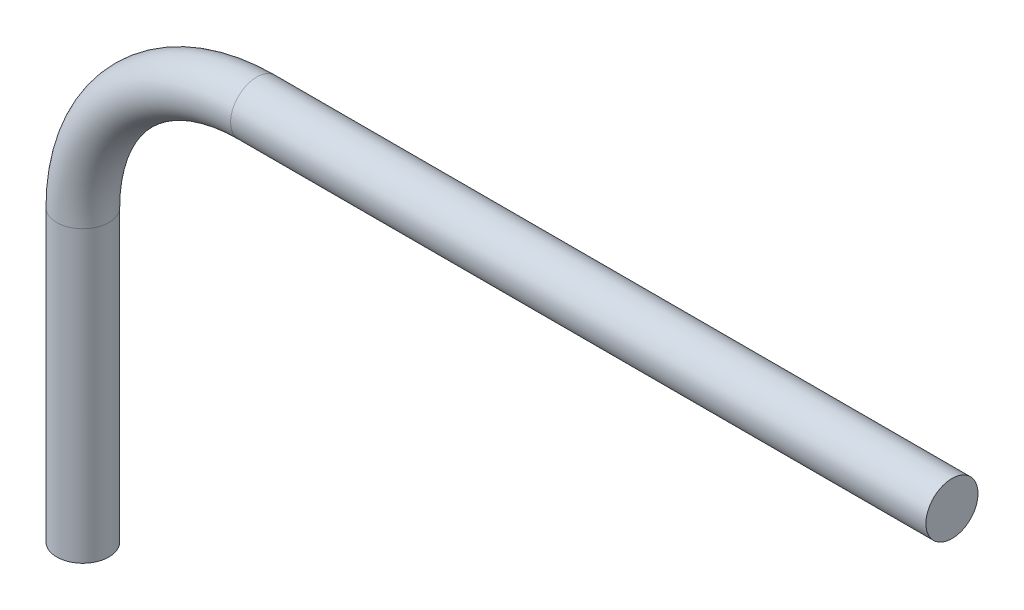
SolidWorks part; units mm, degrees
material "AISI 316 Stainless Steel Sheet (SS)"
ref_plane "Front Plane" through (0, 0, 0) normal (0, 0, 1) x (1, 0, 0)
ref_plane "Top Plane" through (0, 0, 0) normal (0, 1, 0) x (1, 0, 0)
ref_plane "Right Plane" through (0, 0, 0) normal (1, 0, 0) x (0, 0, -1)
sketch "Sketch1" plane through (0, 0, 0) normal (0, 0, 1) x (1, 0, 0)
  line L0 (0, 0) -> (0, 50)
  line L1 (30, 80) -> (150, 80)
  arc A0 (0, 50) -> (30, 80) centre (30, 50) cw
  point P6 (0, 80)
  dimension "D3" = 30
  dimension "D1" = 80
  dimension "D2" = 150
sweep "Sweep1" add path "Sketch1" circular profile diameter 9 parameters "D3"=9
